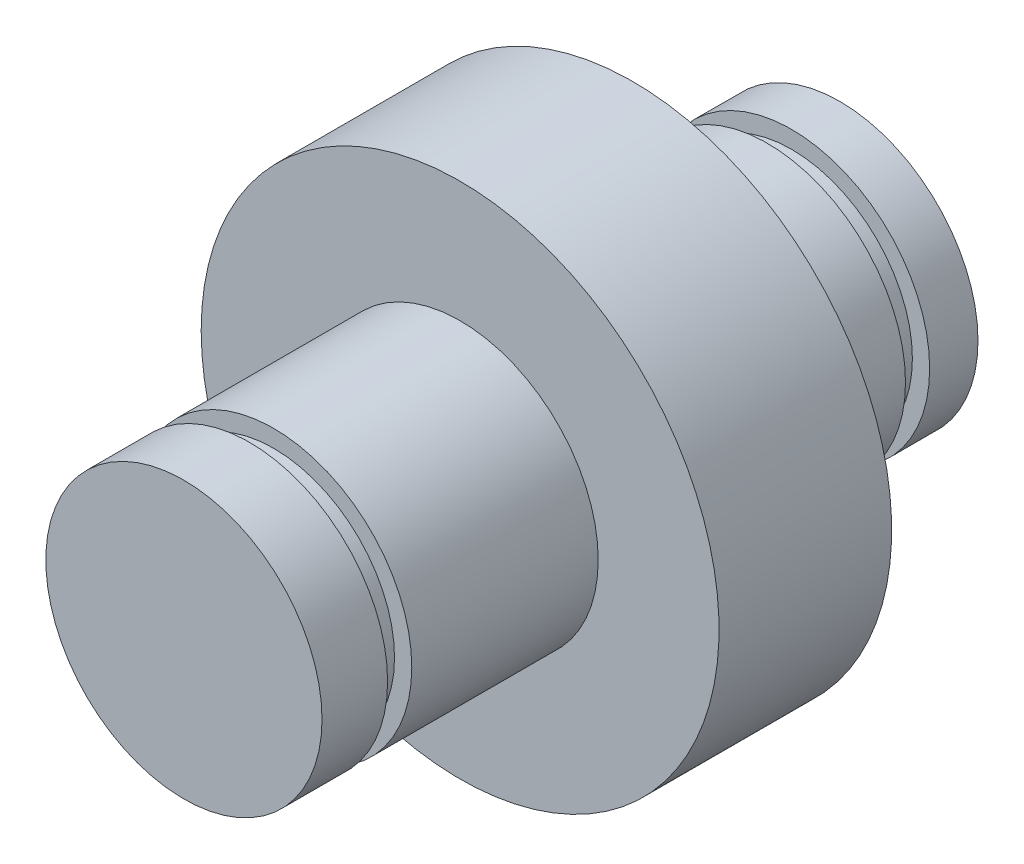
SolidWorks part; units mm, degrees
ref_plane "Front Plane" through (0, 0, 0) normal (0, 0, 1) x (1, 0, 0)
ref_plane "Top Plane" through (0, 0, 0) normal (0, 1, 0) x (1, 0, 0)
ref_plane "Right Plane" through (0, 0, 0) normal (1, 0, 0) x (0, 0, -1)
sketch "Sketch1" plane through (0, 0, 0) normal (0, 0, 1) x (1, 0, 0)
  circle A0 centre (0, 0) radius 4
  dimension "D1" = 8
extrude "Boss-Extrude1" add sketch "Sketch1" along normal blind 8
sketch "Sketch2" plane through (0, 0, 0) normal (0, 0, -1) x (-1, 0, 0)
  circle A0 centre (0, 0) radius 7.5
  dimension "D1" = 15
extrude "Boss-Extrude2" add sketch "Sketch2" along normal blind 5
sketch "Sketch3" plane through (0, 0, -5) normal (0, 0, -1) x (-1, 0, 0)
  circle A0 centre (0, 0) radius 4
  dimension "D1" = 8
extrude "Boss-Extrude3" add sketch "Sketch3" along normal blind 6
sketch "Sketch4" plane through (0, 0, 0) normal (0, 1, 0) x (1, 0, 0)
  line L0 (-4, 0) -> (4, 0) construction
  line L1 (-4, -8) -> (4, -8) construction
  line L2 (-4, 0) -> (-4, -8) construction
  line L3 (-4, 0) -> (4, 0) construction
  line L4 (-4, -8) -> (4, -8) construction
  line L5 (-4, 0) -> (-4, -8) construction
  line L6 (4, 11) -> (-4, 11) construction
  line L7 (-4, -6.1) -> (-3.5, -6.1)
  line L8 (-4, -6.1) -> (-4, -5.4)
  line L9 (-4, -5.4) -> (-3.5, -5.4)
  line L10 (-3.5, -6.1) -> (-3.5, -5.4)
  line L11 (4, 5) -> (-4, 5) construction
  line L12 (-4, 11) -> (-4, 5) construction
  line L13 (4, 11) -> (-4, 11) construction
  line L14 (4, 5) -> (-4, 5) construction
  line L15 (-4, 11) -> (-4, 5) construction
  line L16 (0, 0) -> (0, 16.4702) construction
  line L17 (-4, 8.9) -> (-3.5, 8.9)
  line L18 (-4, 8.9) -> (-4, 9.6)
  line L19 (-4, 9.6) -> (-3.5, 9.6)
  line L20 (-3.5, 8.9) -> (-3.5, 9.6)
  point P16 (-3.75, 9.6)
  dimension "D1" = 0.7
  dimension "D2" = 0.5
  dimension "D3" = 6.1
  dimension "D4" = 0.7
  dimension "D5" = 0.5
  dimension "D6" = 4.6
revolve "Cut-Revolve1" cut sketch "Sketch4" angle 360 about L16
